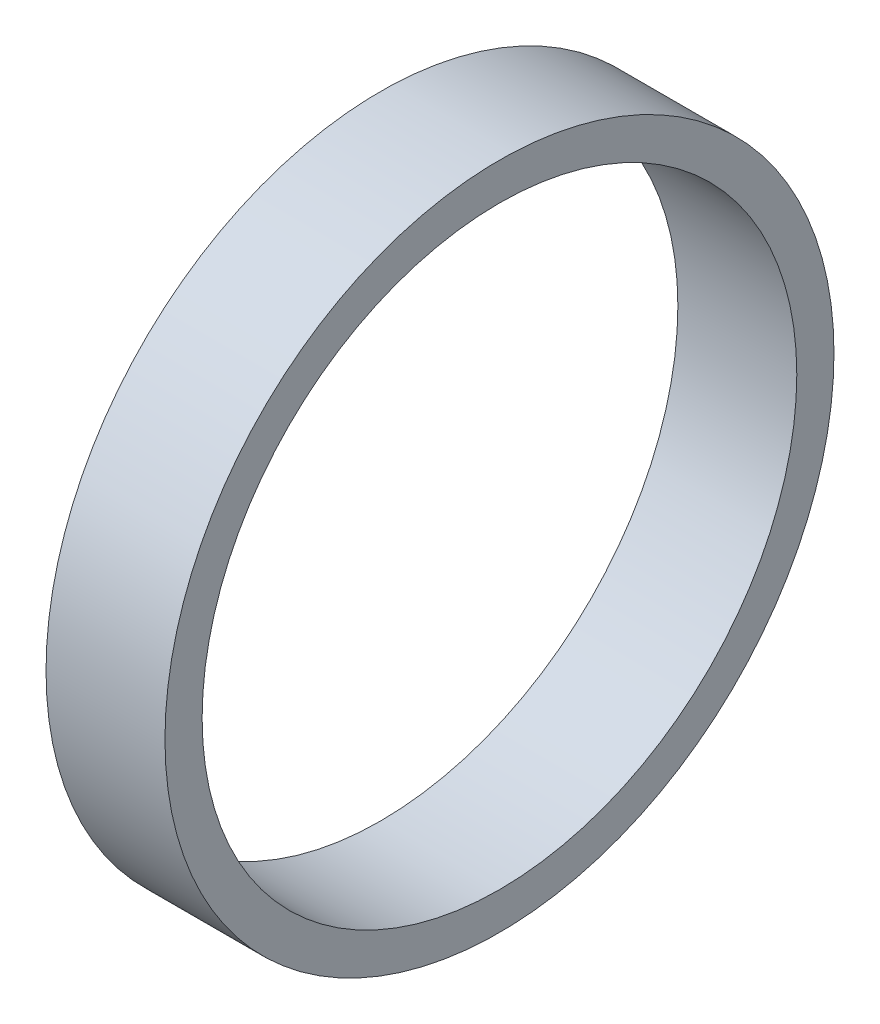
SolidWorks part; units mm, degrees
material "6061-T6 (SS)"
ref_plane "Front Plane" through (0, 0, 0) normal (0, 0, 1) x (1, 0, 0)
ref_plane "Top Plane" through (0, 0, 0) normal (0, 1, 0) x (1, 0, 0)
ref_plane "Right Plane" through (0, 0, 0) normal (1, 0, 0) x (0, 0, -1)
sketch "Sketch1" plane through (0, 0, 0) normal (1, 0, 0) x (0, 0, -1)
  circle A0 centre (0, 0) radius 12.7
  circle A1 centre (0, 0) radius 14.2875
  dimension "D1" = 25.4
  dimension "D2" = 28.575
extrude "Boss-Extrude1" add sketch "Sketch1" along normal blind 5.08
